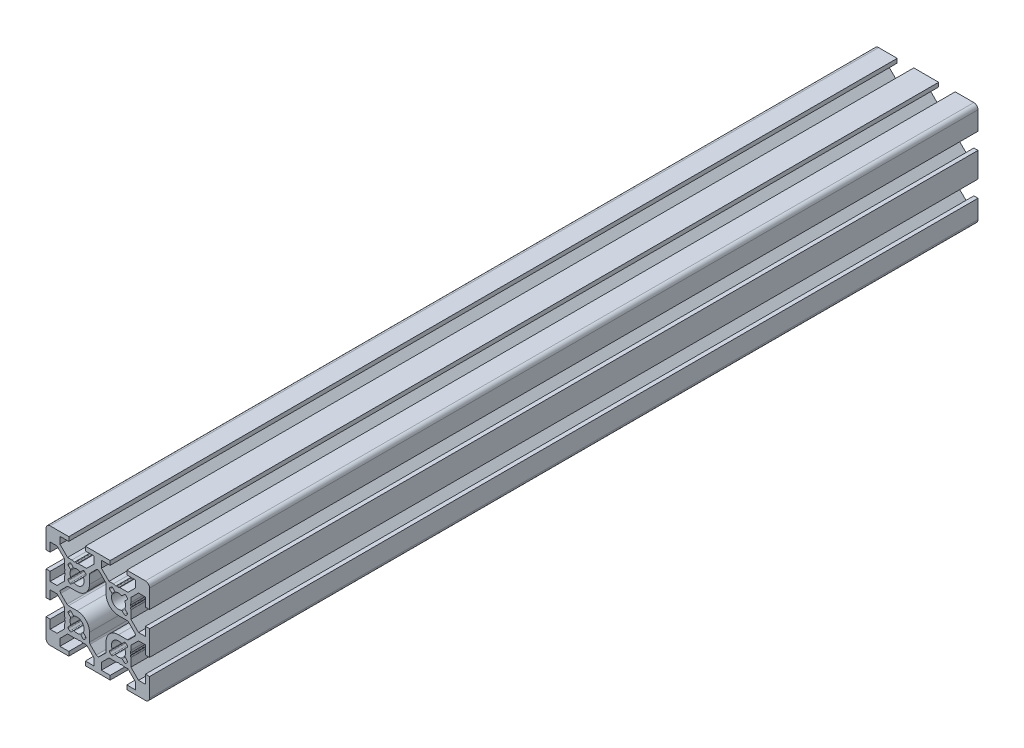
SolidWorks part; units mm, degrees
ref_plane "Front Plane" through (0, 0, 0) normal (0, 0, 1) x (1, 0, 0)
ref_plane "Top Plane" through (0, 0, 0) normal (0, 1, 0) x (1, 0, 0)
ref_plane "Right Plane" through (0, 0, 0) normal (1, 0, 0) x (0, 0, -1)
ref_plane "Plane1" through (0, 0, 0) normal (0, 0, 1) x (1, 0, 0)
sketch "Sketch1" plane through (0, 0, 0) normal (0, 0, 1) x (1, 0, 0)
  line L0 (-25, 23) -> (-25, 14)
  line L1 (-25, 14) -> (-23, 14)
  line L2 (-23, 14) -> (-23, 18.25)
  line L3 (-23, 18.25) -> (-19.6642, 18.25)
  line L4 (-19.6642, 18.25) -> (-16, 14.5858)
  line L5 (-16, 14.5858) -> (-16, 10.6536)
  line L6 (-15.933, 10.4036) -> (-15.7, 10)
  line L7 (-15.7, 10) -> (-15.933, 9.5964)
  line L8 (-15.933, 9.0964) -> (-15.751, 8.7811)
  line L9 (-15.751, 8.7811) -> (-16, 7.5)
  line L10 (-16, 7.5) -> (-16, 5.4142)
  line L11 (-16, 5.4142) -> (-19.6642, 1.75)
  line L12 (-19.6642, 1.75) -> (-23, 1.75)
  line L13 (-23, 1.75) -> (-23, 6)
  line L14 (-23, 6) -> (-25, 6)
  line L15 (-25, 6) -> (-25, -6)
  line L16 (-25, -6) -> (-23, -6)
  line L17 (-23, -6) -> (-23, -1.75)
  line L18 (-23, -1.75) -> (-19.6642, -1.75)
  line L19 (-19.6642, -1.75) -> (-16, -5.4142)
  line L20 (-16, -5.4142) -> (-16, -9.3464)
  line L21 (-15.933, -9.5964) -> (-15.7, -10)
  line L22 (-15.7, -10) -> (-15.933, -10.4036)
  line L23 (-15.933, -10.9036) -> (-15.751, -11.2189)
  line L24 (-15.751, -11.2189) -> (-16, -12.5)
  line L25 (-16, -12.5) -> (-16, -14.5858)
  line L26 (-16, -14.5858) -> (-19.6642, -18.25)
  line L27 (-19.6642, -18.25) -> (-23, -18.25)
  line L28 (-23, -18.25) -> (-23, -14)
  line L29 (-23, -14) -> (-25, -14)
  line L30 (-25, -14) -> (-25, -23)
  line L31 (-23, -25) -> (-14, -25)
  line L32 (-14, -25) -> (-14, -23)
  line L33 (-14, -23) -> (-18.25, -23)
  line L34 (-18.25, -23) -> (-18.25, -19.6642)
  line L35 (-18.25, -19.6642) -> (-14.5858, -16)
  line L36 (-14.5858, -16) -> (-10.6536, -16)
  line L37 (-10.4036, -15.933) -> (-10, -15.7)
  line L38 (-10, -15.7) -> (-9.5964, -15.933)
  line L39 (-9.0964, -15.933) -> (-8.7811, -15.751)
  line L40 (-8.7811, -15.751) -> (-7.5, -16)
  line L41 (-7.5, -16) -> (-5.4142, -16)
  line L42 (-5.4142, -16) -> (-1.75, -19.6642)
  line L43 (-1.75, -19.6642) -> (-1.75, -23)
  line L44 (-1.75, -23) -> (-6, -23)
  line L45 (-6, -23) -> (-6, -25)
  line L46 (-6, -25) -> (6, -25)
  line L47 (6, -25) -> (6, -23)
  line L48 (6, -23) -> (1.75, -23)
  line L49 (1.75, -23) -> (1.75, -19.6642)
  line L50 (1.75, -19.6642) -> (5.4142, -16)
  line L51 (5.4142, -16) -> (9.3464, -16)
  line L52 (9.5964, -15.933) -> (10, -15.7)
  line L53 (10, -15.7) -> (10.4036, -15.933)
  line L54 (10.9036, -15.933) -> (11.2189, -15.751)
  line L55 (11.2189, -15.751) -> (12.5, -16)
  line L56 (12.5, -16) -> (14.5858, -16)
  line L57 (14.5858, -16) -> (18.25, -19.6642)
  line L58 (18.25, -19.6642) -> (18.25, -23)
  line L59 (18.25, -23) -> (14, -23)
  line L60 (14, -23) -> (14, -25)
  line L61 (14, -25) -> (23, -25)
  line L62 (25, -23) -> (25, -14)
  line L63 (25, -14) -> (23, -14)
  line L64 (23, -14) -> (23, -18.25)
  line L65 (23, -18.25) -> (19.6642, -18.25)
  line L66 (19.6642, -18.25) -> (16, -14.5858)
  line L67 (16, -14.5858) -> (16, -10.6536)
  line L68 (15.933, -10.4036) -> (15.7, -10)
  line L69 (15.7, -10) -> (15.933, -9.5964)
  line L70 (15.933, -9.0964) -> (15.751, -8.7811)
  line L71 (15.751, -8.7811) -> (16, -7.5)
  line L72 (16, -7.5) -> (16, -5.4142)
  line L73 (16, -5.4142) -> (19.6642, -1.75)
  line L74 (19.6642, -1.75) -> (23, -1.75)
  line L75 (23, -1.75) -> (23, -6)
  line L76 (23, -6) -> (25, -6)
  line L77 (25, -6) -> (25, 6)
  line L78 (25, 6) -> (23, 6)
  line L79 (23, 6) -> (23, 1.75)
  line L80 (23, 1.75) -> (19.6642, 1.75)
  line L81 (19.6642, 1.75) -> (16, 5.4142)
  line L82 (16, 5.4142) -> (16, 9.3464)
  line L83 (15.933, 9.5964) -> (15.7, 10)
  line L84 (15.7, 10) -> (15.933, 10.4036)
  line L85 (15.933, 10.9036) -> (15.751, 11.2189)
  line L86 (15.751, 11.2189) -> (16, 12.5)
  line L87 (16, 12.5) -> (16, 14.5858)
  line L88 (16, 14.5858) -> (19.6642, 18.25)
  line L89 (19.6642, 18.25) -> (23, 18.25)
  line L90 (23, 18.25) -> (23, 14)
  line L91 (23, 14) -> (25, 14)
  line L92 (25, 14) -> (25, 23)
  line L93 (23, 25) -> (14, 25)
  line L94 (14, 25) -> (14, 23)
  line L95 (14, 23) -> (18.25, 23)
  line L96 (18.25, 23) -> (18.25, 19.6642)
  line L97 (18.25, 19.6642) -> (14.5858, 16)
  line L98 (14.5858, 16) -> (10.6536, 16)
  line L99 (10.4036, 15.933) -> (10, 15.7)
  line L100 (10, 15.7) -> (9.5964, 15.933)
  line L101 (9.0964, 15.933) -> (8.7811, 15.751)
  line L102 (8.7811, 15.751) -> (7.5, 16)
  line L103 (7.5, 16) -> (5.4142, 16)
  line L104 (5.4142, 16) -> (1.75, 19.6642)
  line L105 (1.75, 19.6642) -> (1.75, 23)
  line L106 (1.75, 23) -> (6, 23)
  line L107 (6, 23) -> (6, 25)
  line L108 (6, 25) -> (-6, 25)
  line L109 (-6, 25) -> (-6, 23)
  line L110 (-6, 23) -> (-1.75, 23)
  line L111 (-1.75, 23) -> (-1.75, 19.6642)
  line L112 (-1.75, 19.6642) -> (-5.4142, 16)
  line L113 (-5.4142, 16) -> (-9.3464, 16)
  line L114 (-9.5964, 15.933) -> (-10, 15.7)
  line L115 (-10, 15.7) -> (-10.4036, 15.933)
  line L116 (-10.9036, 15.933) -> (-11.2189, 15.751)
  line L117 (-11.2189, 15.751) -> (-12.5, 16)
  line L118 (-12.5, 16) -> (-14.5858, 16)
  line L119 (-14.5858, 16) -> (-18.25, 19.6642)
  line L120 (-18.25, 19.6642) -> (-18.25, 23)
  line L121 (-18.25, 23) -> (-14, 23)
  line L122 (-14, 23) -> (-14, 25)
  line L123 (-14, 25) -> (-23, 25)
  line L124 (-17.8787, -0.7071) -> (-14.8787, -3.7071)
  line L125 (-14.1716, -4) -> (-10, -4)
  line L126 (-4, -10) -> (-4, -14.1716)
  line L127 (-3.7071, -14.8787) -> (-0.7071, -17.8787)
  line L128 (0.7071, -17.8787) -> (3.7071, -14.8787)
  line L129 (4, -14.1716) -> (4, -10)
  line L130 (10, -4) -> (14.1716, -4)
  line L131 (14.8787, -3.7071) -> (17.8787, -0.7071)
  line L132 (17.8787, 0.7071) -> (14.8787, 3.7071)
  line L133 (14.1716, 4) -> (10, 4)
  line L134 (4, 10) -> (4, 14.1716)
  line L135 (3.7071, 14.8787) -> (0.7071, 17.8787)
  line L136 (-0.7071, 17.8787) -> (-3.7071, 14.8787)
  line L137 (-4, 14.1716) -> (-4, 10)
  line L138 (-10, 4) -> (-14.1716, 4)
  line L139 (-14.8787, 3.7071) -> (-17.8787, 0.7071)
  arc A0 (-16, 10.6536) -> (-15.933, 10.4036) centre (-15.5, 10.6536) ccw
  arc A1 (-15.933, 9.5964) -> (-15.933, 9.0964) centre (-15.5, 9.3464) ccw
  arc A2 (-16, -9.3464) -> (-15.933, -9.5964) centre (-15.5, -9.3464) ccw
  arc A3 (-15.933, -10.4036) -> (-15.933, -10.9036) centre (-15.5, -10.6536) ccw
  arc A4 (-25, -23) -> (-23, -25) centre (-23, -23) ccw
  arc A5 (-10.6536, -16) -> (-10.4036, -15.933) centre (-10.6536, -15.5) ccw
  arc A6 (-9.5964, -15.933) -> (-9.0964, -15.933) centre (-9.3464, -15.5) ccw
  arc A7 (9.3464, -16) -> (9.5964, -15.933) centre (9.3464, -15.5) ccw
  arc A8 (10.4036, -15.933) -> (10.9036, -15.933) centre (10.6536, -15.5) ccw
  arc A9 (23, -25) -> (25, -23) centre (23, -23) ccw
  arc A10 (16, -10.6536) -> (15.933, -10.4036) centre (15.5, -10.6536) ccw
  arc A11 (15.933, -9.5964) -> (15.933, -9.0964) centre (15.5, -9.3464) ccw
  arc A12 (16, 9.3464) -> (15.933, 9.5964) centre (15.5, 9.3464) ccw
  arc A13 (15.933, 10.4036) -> (15.933, 10.9036) centre (15.5, 10.6536) ccw
  arc A14 (25, 23) -> (23, 25) centre (23, 23) ccw
  arc A15 (10.6536, 16) -> (10.4036, 15.933) centre (10.6536, 15.5) ccw
  arc A16 (9.5964, 15.933) -> (9.0964, 15.933) centre (9.3464, 15.5) ccw
  arc A17 (-9.3464, 16) -> (-9.5964, 15.933) centre (-9.3464, 15.5) ccw
  arc A18 (-10.4036, 15.933) -> (-10.9036, 15.933) centre (-10.6536, 15.5) ccw
  arc A19 (-23, 25) -> (-25, 23) centre (-23, 23) ccw
  arc A20 (-17.8787, 0.7071) -> (-17.8787, -0.7071) centre (-17.1716, 0) ccw
  arc A21 (-14.8787, -3.7071) -> (-14.1716, -4) centre (-14.1716, -3) ccw
  arc A22 (-10, -4) -> (-4, -10) centre (-10, -10) cw
  arc A23 (-4, -14.1716) -> (-3.7071, -14.8787) centre (-3, -14.1716) ccw
  arc A24 (-0.7071, -17.8787) -> (0.7071, -17.8787) centre (0, -17.1716) ccw
  arc A25 (3.7071, -14.8787) -> (4, -14.1716) centre (3, -14.1716) ccw
  arc A26 (4, -10) -> (10, -4) centre (10, -10) cw
  arc A27 (14.1716, -4) -> (14.8787, -3.7071) centre (14.1716, -3) ccw
  arc A28 (17.8787, -0.7071) -> (17.8787, 0.7071) centre (17.1716, 0) ccw
  arc A29 (14.8787, 3.7071) -> (14.1716, 4) centre (14.1716, 3) ccw
  arc A30 (10, 4) -> (4, 10) centre (10, 10) cw
  arc A31 (4, 14.1716) -> (3.7071, 14.8787) centre (3, 14.1716) ccw
  arc A32 (0.7071, 17.8787) -> (-0.7071, 17.8787) centre (0, 17.1716) ccw
  arc A33 (-3.7071, 14.8787) -> (-4, 14.1716) centre (-3, 14.1716) ccw
  arc A34 (-4, 10) -> (-10, 4) centre (-10, 10) cw
  arc A35 (-14.1716, 4) -> (-14.8787, 3.7071) centre (-14.1716, 3) ccw
extrude "Boss-Extrude1" add sketch "Sketch1" against normal blind 400
ref_plane "Plane2" through (0, 0, 0) normal (0, 0, 1) x (1, 0, 0)
sketch "Sketch2" plane through (0, 0, 0) normal (0, 0, 1) x (1, 0, 0)
  line L0 (-14.2426, 12.8284) -> (-13.2051, 11.7909)
  line L1 (-13.2051, 8.2091) -> (-14.2426, 7.1716)
  line L2 (-14.2426, 6.4645) -> (-13.5355, 5.7574)
  line L3 (-12.8284, 5.7574) -> (-11.7909, 6.7949)
  line L4 (-6.7949, 11.7909) -> (-5.7574, 12.8284)
  line L5 (-5.7574, 13.5355) -> (-6.4645, 14.2426)
  line L6 (-7.1716, 14.2426) -> (-8.2091, 13.2051)
  line L7 (-11.7909, 13.2051) -> (-12.8284, 14.2426)
  line L8 (-13.5355, 14.2426) -> (-14.2426, 13.5355)
  arc A0 (-14.2426, 13.5355) -> (-14.2426, 12.8284) centre (-13.8891, 13.182) ccw
  arc A1 (-13.2051, 11.7909) -> (-13.1208, 11.3493) centre (-13.4879, 11.508) cw
  arc A2 (-13.1208, 11.3493) -> (-13.1208, 8.6507) centre (-10, 10) ccw
  arc A3 (-13.1208, 8.6507) -> (-13.2051, 8.2091) centre (-13.4879, 8.492) cw
  arc A4 (-14.2426, 7.1716) -> (-14.2426, 6.4645) centre (-13.8891, 6.818) ccw
  arc A5 (-13.5355, 5.7574) -> (-12.8284, 5.7574) centre (-13.182, 6.1109) ccw
  arc A6 (-11.7909, 6.7949) -> (-11.3493, 6.8792) centre (-11.508, 6.5121) cw
  arc A7 (-11.3493, 6.8792) -> (-6.8792, 11.3493) centre (-10, 10) ccw
  arc A8 (-6.8792, 11.3493) -> (-6.7949, 11.7909) centre (-6.5121, 11.508) cw
  arc A9 (-5.7574, 12.8284) -> (-5.7574, 13.5355) centre (-6.1109, 13.182) ccw
  arc A10 (-6.4645, 14.2426) -> (-7.1716, 14.2426) centre (-6.818, 13.8891) ccw
  arc A11 (-8.2091, 13.2051) -> (-8.6507, 13.1208) centre (-8.492, 13.4879) cw
  arc A12 (-8.6507, 13.1208) -> (-11.3493, 13.1208) centre (-10, 10) ccw
  arc A13 (-11.3493, 13.1208) -> (-11.7909, 13.2051) centre (-11.508, 13.4879) cw
  arc A14 (-12.8284, 14.2426) -> (-13.5355, 14.2426) centre (-13.182, 13.8891) ccw
extrude "Cut-Extrude1" cut sketch "Sketch2" against normal through all
ref_plane "Plane3" through (0, 0, 0) normal (0, 0, 1) x (1, 0, 0)
sketch "Sketch3" plane through (0, 0, 0) normal (0, 0, 1) x (1, 0, 0)
  line L0 (-12.8284, -14.2426) -> (-11.7909, -13.2051)
  line L1 (-8.2091, -13.2051) -> (-7.1716, -14.2426)
  line L2 (-6.4645, -14.2426) -> (-5.7574, -13.5355)
  line L3 (-5.7574, -12.8284) -> (-6.7949, -11.7909)
  line L4 (-11.7909, -6.7949) -> (-12.8284, -5.7574)
  line L5 (-13.5355, -5.7574) -> (-14.2426, -6.4645)
  line L6 (-14.2426, -7.1716) -> (-13.2051, -8.2091)
  line L7 (-13.2051, -11.7909) -> (-14.2426, -12.8284)
  line L8 (-14.2426, -13.5355) -> (-13.5355, -14.2426)
  arc A0 (-13.5355, -14.2426) -> (-12.8284, -14.2426) centre (-13.182, -13.8891) ccw
  arc A1 (-11.7909, -13.2051) -> (-11.3493, -13.1208) centre (-11.508, -13.4879) cw
  arc A2 (-11.3493, -13.1208) -> (-8.6507, -13.1208) centre (-10, -10) ccw
  arc A3 (-8.6507, -13.1208) -> (-8.2091, -13.2051) centre (-8.492, -13.4879) cw
  arc A4 (-7.1716, -14.2426) -> (-6.4645, -14.2426) centre (-6.818, -13.8891) ccw
  arc A5 (-5.7574, -13.5355) -> (-5.7574, -12.8284) centre (-6.1109, -13.182) ccw
  arc A6 (-6.7949, -11.7909) -> (-6.8792, -11.3493) centre (-6.5121, -11.508) cw
  arc A7 (-6.8792, -11.3493) -> (-11.3493, -6.8792) centre (-10, -10) ccw
  arc A8 (-11.3493, -6.8792) -> (-11.7909, -6.7949) centre (-11.508, -6.5121) cw
  arc A9 (-12.8284, -5.7574) -> (-13.5355, -5.7574) centre (-13.182, -6.1109) ccw
  arc A10 (-14.2426, -6.4645) -> (-14.2426, -7.1716) centre (-13.8891, -6.818) ccw
  arc A11 (-13.2051, -8.2091) -> (-13.1208, -8.6507) centre (-13.4879, -8.492) cw
  arc A12 (-13.1208, -8.6507) -> (-13.1208, -11.3493) centre (-10, -10) ccw
  arc A13 (-13.1208, -11.3493) -> (-13.2051, -11.7909) centre (-13.4879, -11.508) cw
  arc A14 (-14.2426, -12.8284) -> (-14.2426, -13.5355) centre (-13.8891, -13.182) ccw
extrude "Cut-Extrude2" cut sketch "Sketch3" against normal through all
ref_plane "Plane4" through (0, 0, 0) normal (0, 0, 1) x (1, 0, 0)
sketch "Sketch4" plane through (0, 0, 0) normal (0, 0, 1) x (1, 0, 0)
  line L0 (14.2426, -12.8284) -> (13.2051, -11.7909)
  line L1 (13.2051, -8.2091) -> (14.2426, -7.1716)
  line L2 (14.2426, -6.4645) -> (13.5355, -5.7574)
  line L3 (12.8284, -5.7574) -> (11.7909, -6.7949)
  line L4 (6.7949, -11.7909) -> (5.7574, -12.8284)
  line L5 (5.7574, -13.5355) -> (6.4645, -14.2426)
  line L6 (7.1716, -14.2426) -> (8.2091, -13.2051)
  line L7 (11.7909, -13.2051) -> (12.8284, -14.2426)
  line L8 (13.5355, -14.2426) -> (14.2426, -13.5355)
  arc A0 (14.2426, -13.5355) -> (14.2426, -12.8284) centre (13.8891, -13.182) ccw
  arc A1 (13.2051, -11.7909) -> (13.1208, -11.3493) centre (13.4879, -11.508) cw
  arc A2 (13.1208, -11.3493) -> (13.1208, -8.6507) centre (10, -10) ccw
  arc A3 (13.1208, -8.6507) -> (13.2051, -8.2091) centre (13.4879, -8.492) cw
  arc A4 (14.2426, -7.1716) -> (14.2426, -6.4645) centre (13.8891, -6.818) ccw
  arc A5 (13.5355, -5.7574) -> (12.8284, -5.7574) centre (13.182, -6.1109) ccw
  arc A6 (11.7909, -6.7949) -> (11.3493, -6.8792) centre (11.508, -6.5121) cw
  arc A7 (11.3493, -6.8792) -> (6.8792, -11.3493) centre (10, -10) ccw
  arc A8 (6.8792, -11.3493) -> (6.7949, -11.7909) centre (6.5121, -11.508) cw
  arc A9 (5.7574, -12.8284) -> (5.7574, -13.5355) centre (6.1109, -13.182) ccw
  arc A10 (6.4645, -14.2426) -> (7.1716, -14.2426) centre (6.818, -13.8891) ccw
  arc A11 (8.2091, -13.2051) -> (8.6507, -13.1208) centre (8.492, -13.4879) cw
  arc A12 (8.6507, -13.1208) -> (11.3493, -13.1208) centre (10, -10) ccw
  arc A13 (11.3493, -13.1208) -> (11.7909, -13.2051) centre (11.508, -13.4879) cw
  arc A14 (12.8284, -14.2426) -> (13.5355, -14.2426) centre (13.182, -13.8891) ccw
extrude "Cut-Extrude3" cut sketch "Sketch4" against normal through all
ref_plane "Plane5" through (0, 0, 0) normal (0, 0, 1) x (1, 0, 0)
sketch "Sketch5" plane through (0, 0, 0) normal (0, 0, 1) x (1, 0, 0)
  line L0 (12.8284, 14.2426) -> (11.7909, 13.2051)
  line L1 (8.2091, 13.2051) -> (7.1716, 14.2426)
  line L2 (6.4645, 14.2426) -> (5.7574, 13.5355)
  line L3 (5.7574, 12.8284) -> (6.7949, 11.7909)
  line L4 (11.7909, 6.7949) -> (12.8284, 5.7574)
  line L5 (13.5355, 5.7574) -> (14.2426, 6.4645)
  line L6 (14.2426, 7.1716) -> (13.2051, 8.2091)
  line L7 (13.2051, 11.7909) -> (14.2426, 12.8284)
  line L8 (14.2426, 13.5355) -> (13.5355, 14.2426)
  arc A0 (13.5355, 14.2426) -> (12.8284, 14.2426) centre (13.182, 13.8891) ccw
  arc A1 (11.7909, 13.2051) -> (11.3493, 13.1208) centre (11.508, 13.4879) cw
  arc A2 (11.3493, 13.1208) -> (8.6507, 13.1208) centre (10, 10) ccw
  arc A3 (8.6507, 13.1208) -> (8.2091, 13.2051) centre (8.492, 13.4879) cw
  arc A4 (7.1716, 14.2426) -> (6.4645, 14.2426) centre (6.818, 13.8891) ccw
  arc A5 (5.7574, 13.5355) -> (5.7574, 12.8284) centre (6.1109, 13.182) ccw
  arc A6 (6.7949, 11.7909) -> (6.8792, 11.3493) centre (6.5121, 11.508) cw
  arc A7 (6.8792, 11.3493) -> (11.3493, 6.8792) centre (10, 10) ccw
  arc A8 (11.3493, 6.8792) -> (11.7909, 6.7949) centre (11.508, 6.5121) cw
  arc A9 (12.8284, 5.7574) -> (13.5355, 5.7574) centre (13.182, 6.1109) ccw
  arc A10 (14.2426, 6.4645) -> (14.2426, 7.1716) centre (13.8891, 6.818) ccw
  arc A11 (13.2051, 8.2091) -> (13.1208, 8.6507) centre (13.4879, 8.492) cw
  arc A12 (13.1208, 8.6507) -> (13.1208, 11.3493) centre (10, 10) ccw
  arc A13 (13.1208, 11.3493) -> (13.2051, 11.7909) centre (13.4879, 11.508) cw
  arc A14 (14.2426, 12.8284) -> (14.2426, 13.5355) centre (13.8891, 13.182) ccw
extrude "Cut-Extrude4" cut sketch "Sketch5" against normal through all
